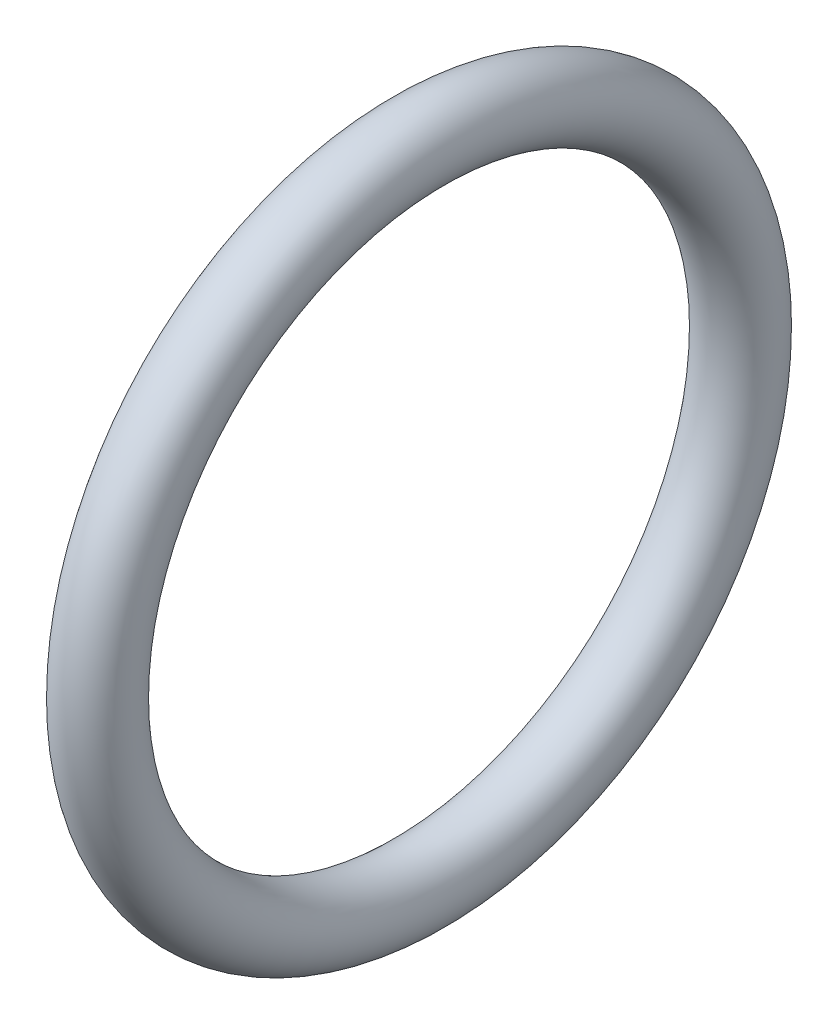
SolidWorks part; units mm, degrees
ref_plane "前视基准面" through (0, 0, 0) normal (0, 0, 1) x (1, 0, 0)
ref_plane "上视基准面" through (0, 0, 0) normal (0, 1, 0) x (1, 0, 0)
ref_plane "右视基准面" through (0, 0, 0) normal (1, 0, 0) x (0, 0, -1)
sketch "草图1" plane through (0, 0, 0) normal (0, 0, 1) x (1, 0, 0)
  line L0 (0, 0) -> (24.9916, 0) construction
  circle A0 centre (0, 14.25) radius 1.6
  dimension "D1" = 3.2
  dimension "D2" = 14.25
revolve "旋转1" add sketch "草图1" angle 360 about L0
